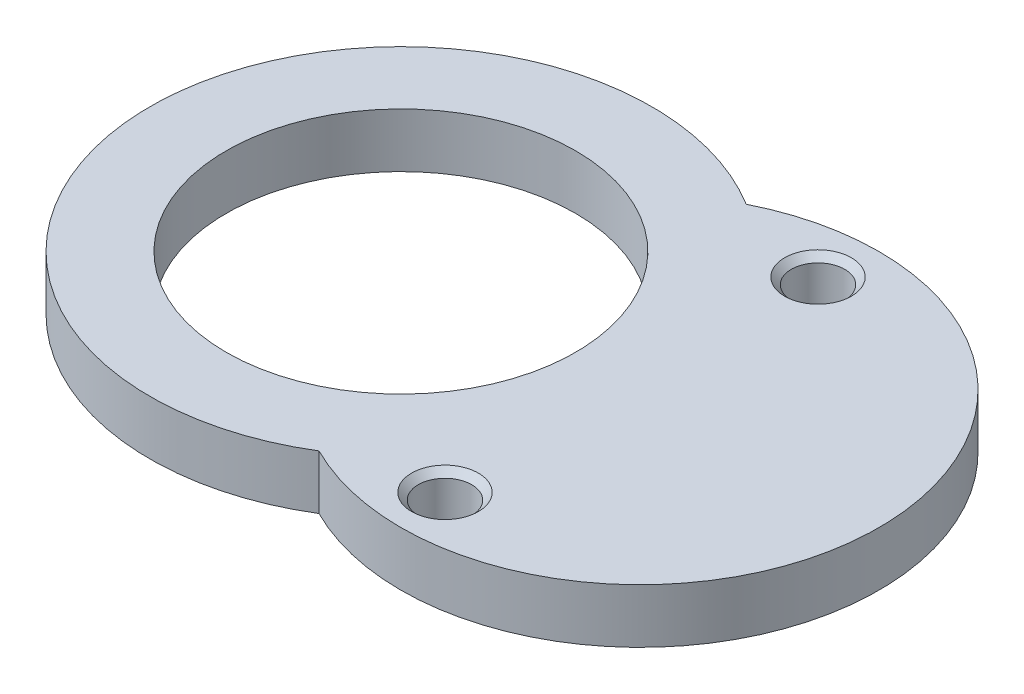
SolidWorks part; units mm, degrees
material "AISI Type A2 Tool Steel"
ref_plane "Front" through (0, 0, 0) normal (0, 0, 1) x (1, 0, 0)
ref_plane "Top" through (0, 0, 0) normal (0, 1, 0) x (1, 0, 0)
ref_plane "Right" through (0, 0, 0) normal (1, 0, 0) x (0, 0, -1)
sketch "Sketch1" plane through (0, 0, 0) normal (0, 1, 0) x (1, 0, 0)
  line L0 (-9.398, 0) -> (17.907, 0) construction
  line L1 (8.9535, 0) -> (17.907, 0) construction
  arc A0 (4.9323, 7.9997) -> (4.9323, -7.9997) centre (0, 0) ccw
  arc A1 (4.9323, -7.9997) -> (4.9323, 7.9997) centre (8.9535, 0) ccw
  dimension "D1" = 18.796
  dimension "D3" = 17.907
  dimension "D2" = 27.305
extrude "Boss-Extrude1" add sketch "Sketch1" along normal blind 2.032
sketch "Sketch2" plane through (0, 2.032, 0) normal (0, 1, 0) x (1, 0, 0)
  circle A0 centre (0, 0) radius 6.5405
  dimension "D1" = 13.081
extrude "Cut-Extrude1" cut sketch "Sketch2" against normal through all
hole_wizard "CSK for M2 Flat Head Machine Screw1" positions "Sketch5" profile "Sketch4" countersink size "M2" standard "ANSI Metric" end condition through all
sketch "Sketch5" plane through (0, 2.032, 0) normal (0, 1, 0) x (1, 0, 0)
  line L0 (17.907, 0) -> (8.636, 0) construction
  line L2 (8.636, 6.985) -> (8.636, -6.985) construction
  arc A0 (4.9323, -7.9997) -> (4.9323, 7.9997) centre (8.9535, 0) ccw construction
  point P0 (8.636, 6.985)
  point P2 (8.636, -6.985)
  point P18 (8.636, 0)
  dimension "D1" = 9.271
  dimension "D2" = 13.97
sketch "Sketch4" plane through (8.636, 2.032, -6.985) normal (1, 0, 0) x (0, 0, 1)
  line L0 (0, 0) -> (0, 2.032)
  line L1 (0, 2.032) -> (1, 2.032)
  line L2 (1, 2.032) -> (1, 0.25)
  line L3 (1, 0.25) -> (1.25, 0)
  line L5 (1.25, 0) -> (0, 0)
  line L6 (-1, 0.25) -> (-1.25, 0) construction
  line L11 (0, -6.35) -> (0, 107.95) construction
  dimension "Thru Hole Dia." = 2
  dimension "Thru Hole Depth" = 2.032
  dimension "Near C'Sink Dia." = 2.5
  dimension "Near C'Sink Angle" = 90
